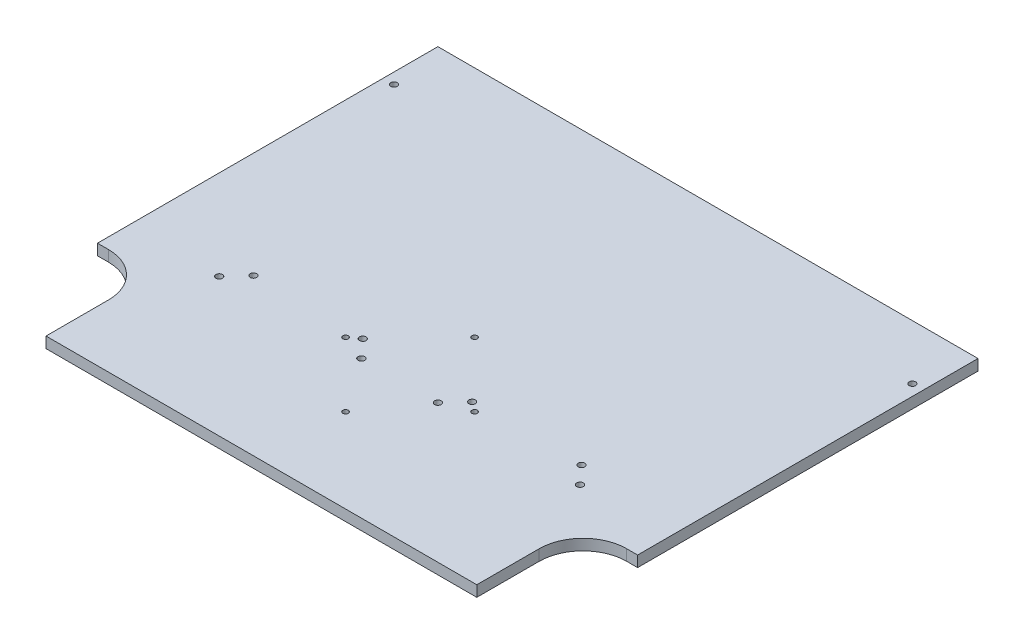
SolidWorks part; units mm, degrees
material "ABS PC"
ref_plane "Plan de face" through (0, 0, 0) normal (0, 0, 1) x (1, 0, 0)
ref_plane "Plan de dessus" through (0, 0, 0) normal (0, 1, 0) x (1, 0, 0)
ref_plane "Plan de droite" through (0, 0, 0) normal (1, 0, 0) x (0, 0, -1)
sketch "Esquisse1" plane through (0, 0, 0) normal (0, 1, 0) x (1, 0, 0)
  line L1 (123.5, -119.4649) -> (123.5, 31.2) construction
  line L2 (123.5, -119.4649) -> (123.5, 36.2)
  line L3 (-123.5, -119.4649) -> (-123.5, 31.2) construction
  line L4 (-123.5, -119.4649) -> (-123.5, 36.2)
  line L6 (123.5, -119.4649) -> (118.5, -119.4649)
  line L7 (98.5, -139.4649) -> (98.5, -168)
  line L9 (98.5, -168) -> (-98.5, -168)
  line L10 (-98.5, -168) -> (-98.5, -139.4649)
  line L11 (-118.5, -119.4649) -> (-123.5, -119.4649)
  line L13 (-115.5, -168) -> (115.5, -168) construction
  line L14 (0, 0) -> (0, -244.9161) construction
  line L17 (123.5, 36.2) -> (-123.5, 36.2)
  line L19 (123.5, 36.2) -> (-123.5, 36.2) construction
  arc A1 (118.5, -119.4649) -> (98.5, -139.4649) centre (118.5, -139.4649) ccw
  arc A6 (-98.5, -139.4649) -> (-118.5, -119.4649) centre (-118.5, -139.4649) ccw
  circle A8 centre (118.5, -139.4649) radius 15.5 construction
  dimension "D1" = 20
extrude "Boss.-Extru.1" add sketch "Esquisse1" against normal blind 5
sketch "Esquisse2" plane through (0, 0, 0) normal (0, 1, 0) x (1, 0, 0)
  circle A0 centre (-118.5, 11.2) radius 1.5
  circle A2 centre (118.5, 11.2) radius 1.5
  dimension "D1" = 3
extrude "Enlèv. mat.-Extru.1" cut sketch "Esquisse2" against normal through all
sketch "Esquisse4" plane through (0, 0, 0) normal (0, 1, 0) x (1, 0, 0)
  circle A1 centre (0, -129.5) radius 1.25 construction
  circle A3 centre (0, -129.5) radius 1.25
  circle A4 centre (29.5, -100) radius 1.25 construction
  circle A5 centre (29.5, -100) radius 1.25
  circle A6 centre (-29.5, -100) radius 1.25 construction
  circle A7 centre (-29.5, -100) radius 1.25
  circle A8 centre (0, -70.5) radius 1.25 construction
  circle A9 centre (0, -70.5) radius 1.25
extrude "Enlèv. mat.-Extru.3" cut sketch "Esquisse4" against normal through all
sketch "Esquisse5" plane through (0, -179.4241, 11.214) normal (0, 0.9981, -0.0624) x (1, 0, 0)
  circle A0 centre (-17.5, -104.5834) radius 1.5 construction
  circle A1 centre (-25, -96.4515) radius 1.5 construction
  circle A2 centre (-17.5, -104.5834) radius 1.5
  circle A3 centre (-25, -96.4515) radius 1.5
  circle A4 centre (-82.5, -104.5834) radius 1.5 construction
  circle A5 centre (-75, -96.4515) radius 1.5 construction
  circle A6 centre (-82.5, -104.5834) radius 1.5
  circle A7 centre (-75, -96.4515) radius 1.5
  circle A8 centre (17.5, -104.5834) radius 1.5 construction
  circle A9 centre (25, -96.4515) radius 1.5 construction
  circle A10 centre (17.5, -104.5834) radius 1.5
  circle A11 centre (25, -96.4515) radius 1.5
  circle A12 centre (75, -96.4515) radius 1.5 construction
  circle A13 centre (82.5, -104.5834) radius 1.5 construction
  circle A14 centre (75, -96.4515) radius 1.5
  circle A15 centre (82.5, -104.5834) radius 1.5
extrude "Enlèv. mat.-Extru.6" cut sketch "Esquisse5" along normal through all
